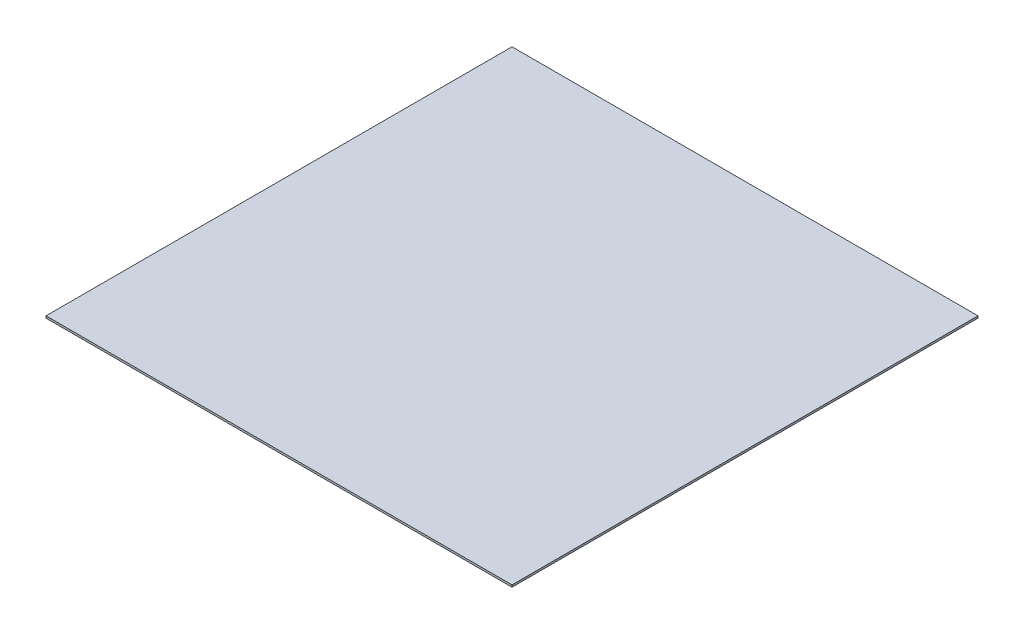
SolidWorks part; units mm, degrees
ref_plane "Front Plane" through (0, 0, 0) normal (0, 0, 1) x (1, 0, 0)
ref_plane "Top Plane" through (0, 0, 0) normal (0, 1, 0) x (1, 0, 0)
ref_plane "Right Plane" through (0, 0, 0) normal (1, 0, 0) x (0, 0, -1)
sketch "Sketch1" plane through (0, 0, 0) normal (0, 1, 0) x (1, 0, 0)
  line L1 (-150, 150) -> (150, 150)
  line L2 (-150, 150) -> (-150, -150)
  line L3 (-150, -150) -> (150, -150)
  line L4 (150, 150) -> (150, -150)
  line L5 (-150, 150) -> (150, -150) construction
  line L6 (-150, -150) -> (150, 150) construction
  point P0 (0, 0)
  dimension "D1" = 300
extrude "Boss-Extrude1" add sketch "Sketch1" along normal blind 1.3
